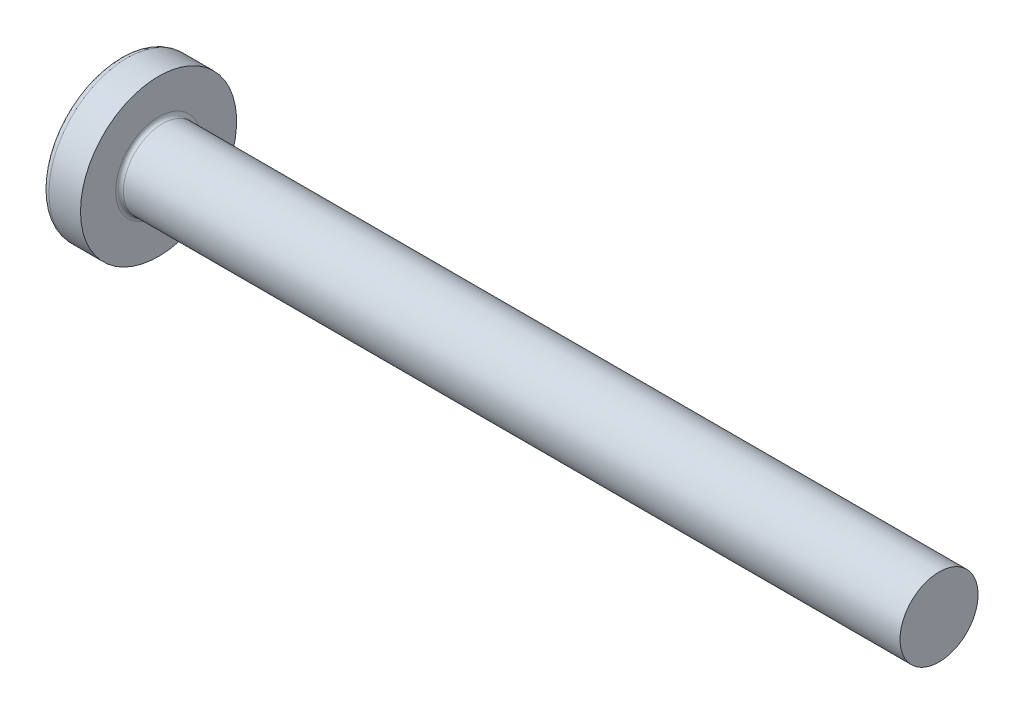
SolidWorks part; units mm, degrees
ref_plane "Plane1" through (0, 0, 0) normal (0, 0, 1) x (1, 0, 0)
ref_plane "Plane2" through (0, 0, 0) normal (0, 1, 0) x (1, 0, 0)
ref_plane "Plane3" through (0, 0, 0) normal (1, 0, 0) x (0, 0, -1)
sketch "BodySke" plane through (0, 0, 0) normal (0, 0, 1) x (1, 0, 0)
  line L0 (1.6, 1) -> (1.6, 2)
  line L1 (1.8, 6.35) -> (1.8, -3.175) construction
  line L2 (-25.4, 0) -> (127, 0) construction
  line L3 (21.6, 0) -> (0, 0)
  line L4 (1.6, 1) -> (21.6, 1)
  line L5 (21.6, 1) -> (21.6, 0)
  line L6 (0.79, 2) -> (1.6, 2)
  line L8 (1.6, 6.35) -> (1.6, -3.175) construction
  arc A0 (0.6464, 1.9285) -> (0, 0) centre (3.2, 0) ccw
  arc A2 (0.6464, 1.9285) -> (0.79, 2) centre (0.79, 1.82) cw
  dimension "Head_crown_rad" = 3.2
  dimension "Head_fillet_rad" = 0.18
  dimension "Length" = 20
  dimension "Head_ht" = 1.6
  dimension "Head_dia" = 4
  dimension "Advance" = 0.4
  dimension "Thread_nom" = 20
  dimension "Diameter" = 2
revolve "Base-Revolve" add sketch "BodySke"
cosmetic thread "ThreadCosmetic" [suppressed]
fillet "Fillet1" radius 0.1 1 edges at (1.6, 0, 1)
sketch "Sketch3" plane through (0, 0, 0) normal (1, 0, 0) x (0, 0, -1)
  line L0 (0.24, -1.05) -> (-0.24, -1.05)
  line L1 (0.24, -1.05) -> (0.24, 1.05)
  line L2 (-0.24, 1.05) -> (0.24, 1.05)
  line L3 (-0.24, 1.05) -> (-0.24, -1.05)
  dimension "Cross_dia" = 2.1
  dimension "D1" = 1.05
  dimension "Cross_width" = 0.48
  dimension "D2" = 0.24
ref_plane "Plane4" through (1.42, 0, 0) normal (1, 0, 0) x (0, 0, -1)
sketch "Sketch4" plane through (1.42, 0, 0) normal (1, 0, 0) x (0, 0, -1)
  line L0 (0.24, -0.342) -> (-0.24, -0.342)
  line L1 (0.24, -0.342) -> (0.24, 0.342)
  line L2 (-0.24, 0.342) -> (0.24, 0.342)
  line L3 (-0.24, 0.342) -> (-0.24, -0.342)
  dimension "D1" = 0.48
  dimension "D2" = 0.684
  dimension "D3" = 0.24
  dimension "D4" = 0.342
loft "Recess" cut profiles "Sketch3", "Sketch4"
pattern_circular "RecPat" count 2 every 90 about axis through (0, 0, 0) along (1, 0, 0) of "Recess"
sketch "RecCorSke" plane through (0, 0, 0) normal (0, 0, 1) x (1, 0, 0)
  line L0 (-3.175, 0) -> (15.875, 0) construction
  line L1 (-25.4, 0) -> (127, 0) construction
  line L2 (0, 0) -> (0, 0.4548)
  line L3 (0, 0.4548) -> (1.42, 0.3555)
  line L4 (1.42, 0.3555) -> (1.5355, 0)
  line L5 (1.5355, 0) -> (0, 0)
  dimension "Diameter" = 0.711
  dimension "Depth" = 1.42
  dimension "Draft_angle" = 4
  dimension "Bottom_angle" = 18
revolve "RecessCore" cut sketch "RecCorSke" angle 360 about L0
sketch "ThdSchSke" plane through (0, 0, 0) normal (0, 0, 1) x (1, 0, 0)
  line L0 (2.4, -0.774) -> (2.2418, -1)
  line L1 (2.4, -0.774) -> (2.5582, -1)
  line L2 (2.5582, -1) -> (2.5582, -1.25)
  line L3 (-3.175, 0) -> (5.1513, 0) construction
  line L5 (2.5582, -1.25) -> (2.2418, -1.25)
  line L6 (2.2418, -1.25) -> (2.2418, -1)
  dimension "Diameter" = 2
  dimension "SideAngle" = 55
  dimension "VeeAngle" = 70
  dimension "Thread_minor" = 1.548
  dimension "Overcut" = 2.5
  dimension "Start" = 2.4
revolve "ThreadSchematic" [suppressed] cut sketch "ThdSchSke" angle 360 about L3
pattern_linear "ThdSchPat" [suppressed]
equation "\"D1@Sketch3\" = \"Cross_dia@Sketch3\" / 2"
equation "\"D2@Sketch3\" = \"Cross_width@Sketch3\" / 2"
equation "\"Depth@RecCorSke\" = \"Cross_depth@Plane4\""
equation "\"D1@Sketch4\" = \"Cross_width@Sketch3\""
equation "\"D2@Sketch4\" = \"Cross_dia@Sketch3\" - 2.0 * \"Cross_depth@Plane4\" * tan(26.5  * 0.017453292)"
equation "\"D3@Sketch4\" = \"D1@Sketch4\" / 2"
equation "\"D4@Sketch4\" = \"D2@Sketch4\" / 2"
equation "\"Thread_length@ThreadCosmetic\" = ((sgn( (\"Length@BodySke\" - \"Advance@BodySke\" * 2.0 ) - \"Thread_nom@BodySke\" )-1)*( (\"Length@BodySke\" - \"Advance@BodySke\" * 2.0 ) - \"Thread_nom@BodySke\" ))/-2+ \"Thread_nom@BodySke\""
equation "\"Thread_minor@ThdSchSke\" = \"Thread_minor@ThreadCosmetic\""
equation "\"Diameter@ThdSchSke\" = \"Diameter@BodySke\""
equation "\"Overcut@ThdSchSke\" = \"Diameter@BodySke\" * 1.25"
equation "\"Start@ThdSchSke\" = \"Head_ht@BodySke\" + \"Length@BodySke\" - \"Thread_length@ThreadCosmetic\"  '---Non-countersunk---"
equation "\"Num_threads@ThdSchPat\" = int( \"Thread_length@ThreadCosmetic\" / \"Advance@BodySke\" + 0.999 )  + 1"
equation "\"Advance@ThdSchPat\" = \"Thread_length@ThreadCosmetic\" /  (\"Num_threads@ThdSchPat\" - 1) 'relax it"
